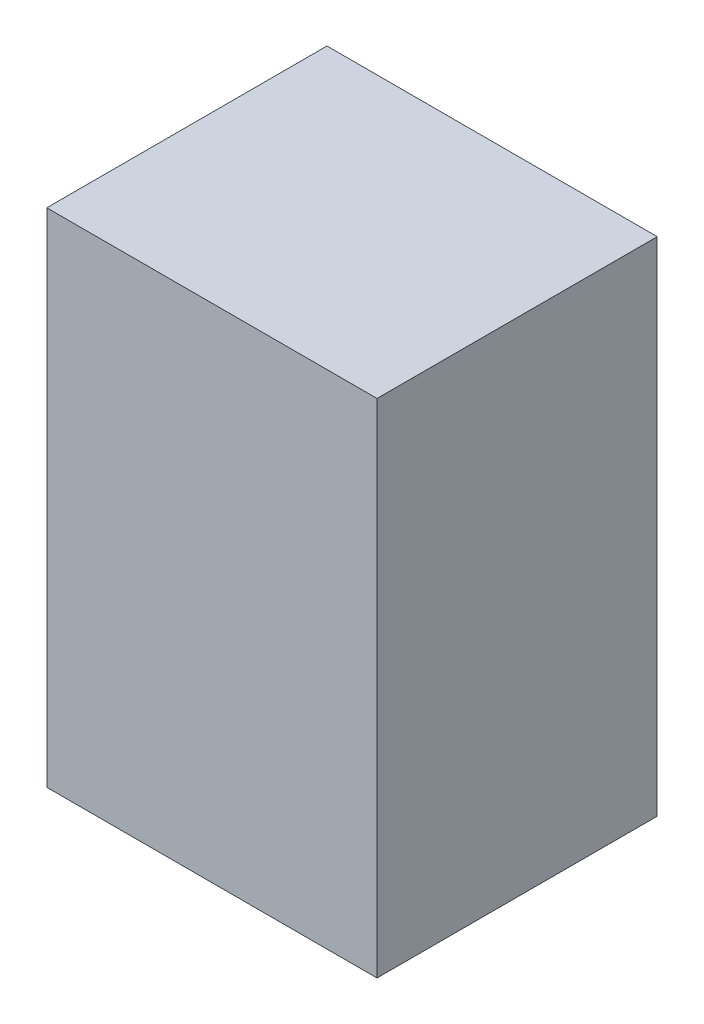
SolidWorks part; units mm, degrees
ref_plane "Front Plane" through (0, 0, 0) normal (0, 0, 1) x (1, 0, 0)
ref_plane "Top Plane" through (0, 0, 0) normal (0, 1, 0) x (1, 0, 0)
ref_plane "Right Plane" through (0, 0, 0) normal (1, 0, 0) x (0, 0, -1)
sketch "Sketch1" plane through (0, 0, 0) normal (0, 0, 1) x (1, 0, 0)
  line L1 (-33, -50.15) -> (33, -50.15)
  line L2 (-33, -50.15) -> (-33, 50.15)
  line L3 (-33, 50.15) -> (33, 50.15)
  line L4 (33, -50.15) -> (33, 50.15)
  line L5 (-33, -50.15) -> (33, 50.15) construction
  line L6 (-33, 50.15) -> (33, -50.15) construction
  point P0 (0, 0)
  dimension "D1" = 100.3
  dimension "D2" = 66
extrude "Boss-Extrude1" add sketch "Sketch1" along normal mid plane 56
